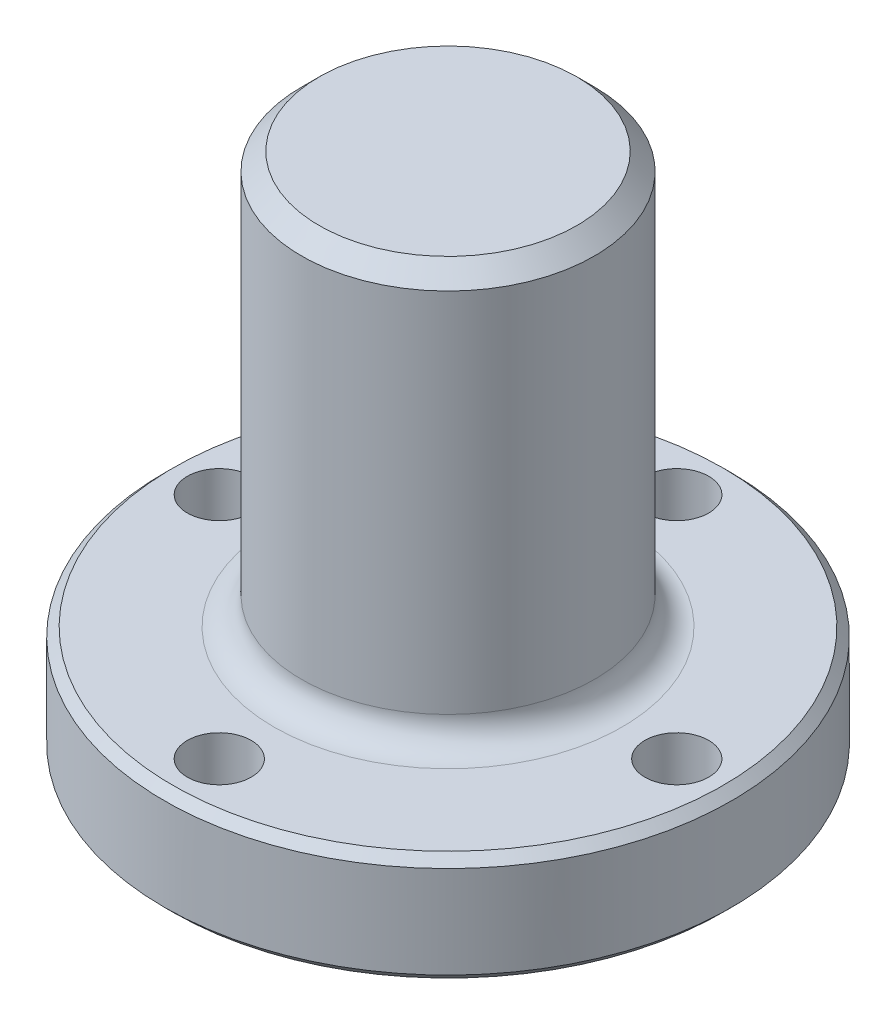
SolidWorks part; units mm, degrees
ref_plane "Front Plane" through (0, 0, 0) normal (1, 0, 0) x (0, 1, 0)
ref_plane "Top Plane" through (0, 0, 0) normal (0, 0, 1) x (0, 1, 0)
ref_plane "Right Plane" through (0, 0, 0) normal (0, 1, 0) x (-1, 0, 0)
sketch "Sketch1" plane through (0, 0, 0) normal (0, 0, 1) x (0, 1, 0)
  line L0 (-25.0317, 0) -> (-25.0317, 8.7122)
  line L1 (-25.0317, 8.7122) -> (-20.2057, 8.7122)
  line L2 (-20.2057, 8.7122) -> (-20.2057, 24.6126)
  line L3 (-20.2057, 24.6126) -> (-10.6807, 24.6126)
  line L4 (-10.6807, 24.6126) -> (-10.6807, 12.7)
  line L5 (-10.6807, 12.7) -> (25.0317, 12.7)
  line L6 (25.0317, 12.7) -> (25.0317, 0)
  line L7 (25.0317, 0) -> (-25.0317, 0)
  line L8 (-50.4317, 0) -> (50.4317, 0) construction
revolve "Revolve1" add sketch "Sketch1" angle 360 about L8
sketch "Sketch2" plane through (0, 0, 0) normal (0, 1, 0) x (-1, 0, 0)
  circle A0 centre (19.8374, 0) radius 2.7686
  circle A1 centre (0, 19.8374) radius 2.7686
  circle A2 centre (-19.8374, 0) radius 2.7686
  circle A3 centre (0, -19.8374) radius 2.7686
extrude "Cut-Extrude2" cut sketch "Sketch2" along normal blind 20.2057 from offset 20.2057
fillet "Fillet1" radius 2.3876 1 edges at (0, -10.6807, -12.7)
chamfer "Chamfer1" distance 0.762 angle 45 2 edges at (0, -10.6807, -24.6126) (0, -20.2057, -24.6126)
chamfer "Chamfer2" distance 1.524 angle 45 1 edges at (0, 25.0317, -12.7)
